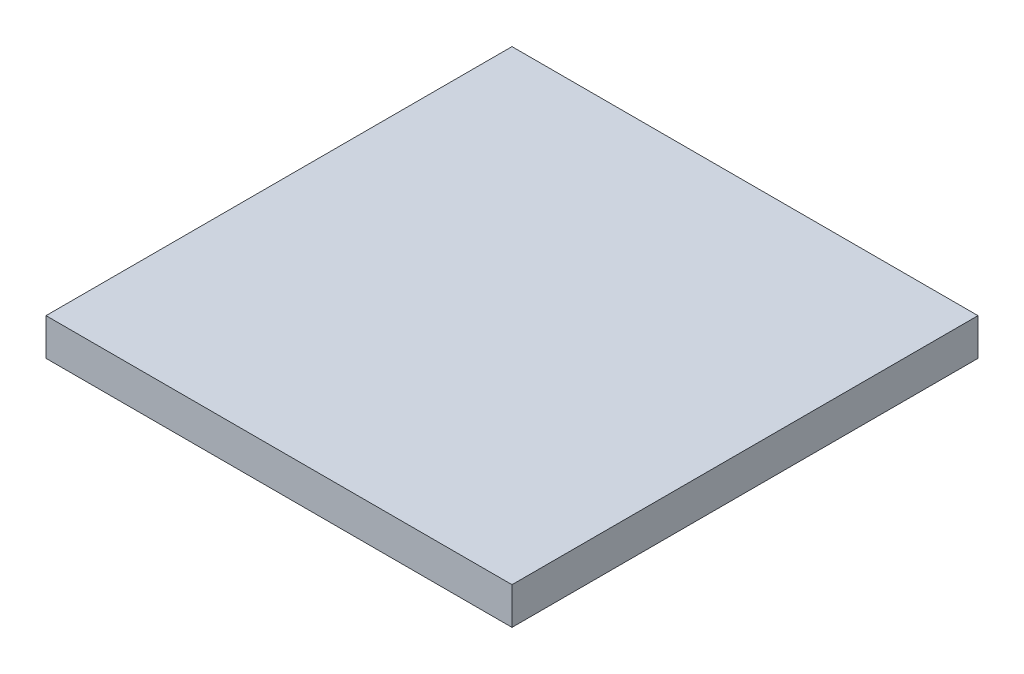
SolidWorks part; units mm, degrees
ref_plane "Front Plane" through (0, 0, 0) normal (0, 0, 1) x (1, 0, 0)
ref_plane "Top Plane" through (0, 0, 0) normal (0, 1, 0) x (1, 0, 0)
ref_plane "Right Plane" through (0, 0, 0) normal (1, 0, 0) x (0, 0, -1)
sketch "Sketch2" plane through (0, 0, 0) normal (0, 1, 0) x (1, 0, 0)
  line L1 (13.1143, 29.3104) -> (45.0929, 29.3104)
  line L2 (13.1143, 29.3104) -> (13.1143, -2.6682)
  line L3 (13.1143, -2.6682) -> (45.0929, -2.6682)
  line L4 (45.0929, 29.3104) -> (45.0929, -2.6682)
  dimension "D1" = 31.9786
  dimension "D2" = 31.9786
extrude "Boss-Extrude1" add sketch "Sketch2" along normal blind 2.54
